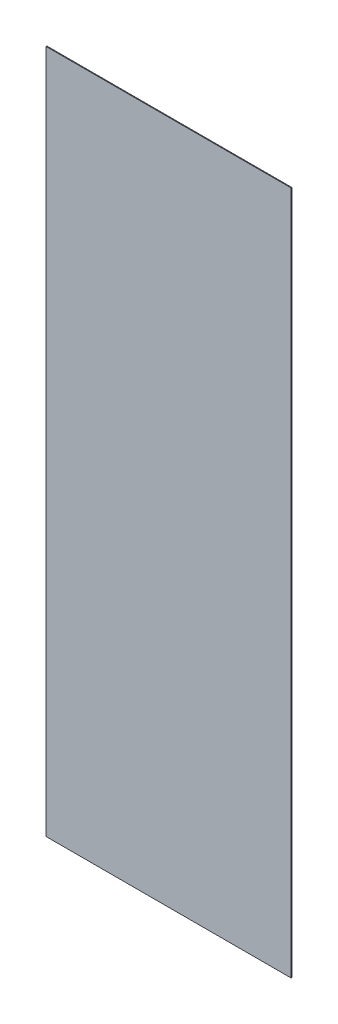
SolidWorks part; units mm, degrees
ref_plane "Front Plane" through (0, 0, 0) normal (0, 0, 1) x (1, 0, 0)
ref_plane "Top Plane" through (0, 0, 0) normal (0, 1, 0) x (1, 0, 0)
ref_plane "Right Plane" through (0, 0, 0) normal (1, 0, 0) x (0, 0, -1)
other "Configuration Table"
sketch "Sketch1" plane through (0, 0, 0) normal (0, 0, 1) x (1, 0, 0)
  line L1 (42.5, 242.5) -> (657.5, 242.5)
  line L2 (42.5, 242.5) -> (42.5, 1960)
  line L3 (42.5, 1960) -> (657.5, 1960)
  line L4 (657.5, 242.5) -> (657.5, 1960)
extrude "TOPPING_arka_duvar_kapak_saci_1" add sketch "Sketch1" against normal blind 2 from offset 720 separate body
